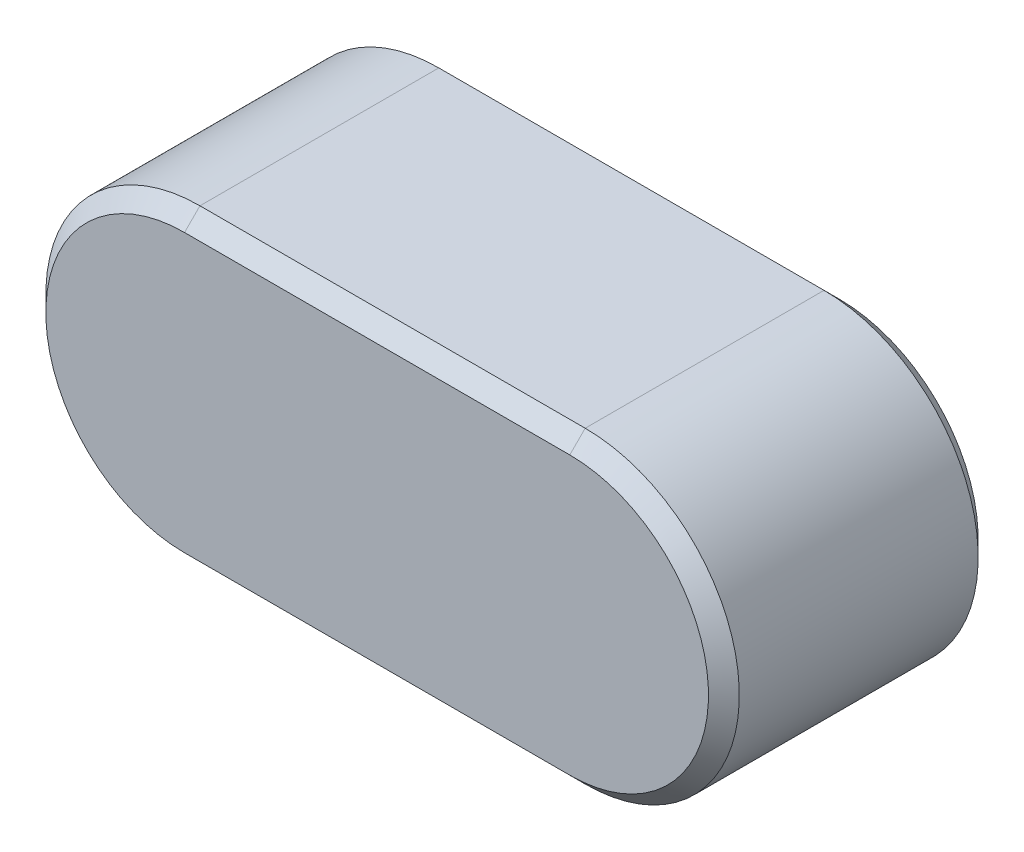
SolidWorks part; units mm, degrees
ref_plane "Front" through (0, 0, 0) normal (0, 0, 1) x (1, 0, 0)
ref_plane "Top" through (0, 0, 0) normal (0, 1, 0) x (1, 0, 0)
ref_plane "Right" through (0, 0, 0) normal (1, 0, 0) x (0, 0, -1)
other "Configuration Table"
sketch "Sketch1" plane through (0, 0, 0) normal (0, 0, 1) x (1, 0, 0)
  line L0 (-10, 4) -> (0, 4)
  line L1 (0, -4) -> (-10, -4)
  arc A0 (0, 4) -> (0, -4) centre (0, 0) cw
  arc A1 (-10, -4) -> (-10, 4) centre (-10, 0) cw
  dimension "L" = 18
  dimension "b" = 8
extrude "BaseKey" add sketch "Sketch1" along normal mid plane 7
sketch "Sketch2" plane through (0, 0, 0) normal (0, 0, 1) x (1, 0, 0)
  line L1 (-14, 4) -> (4, 4)
  line L2 (-14, 4) -> (-14, -4)
  line L3 (-14, -4) -> (4, -4)
  line L4 (4, 4) -> (4, -4)
  line L6 (0, -4) -> (-10, -4) construction
  line L7 (-10, 4) -> (0, 4) construction
  arc A2 (0, -4) -> (0, 4) centre (0, 0) ccw construction
  arc A3 (-10, 4) -> (-10, -4) centre (-10, 0) ccw construction
extrude "Extrude1" [suppressed] add sketch "Sketch2" along normal mid plane 7
sketch "Sketch3" plane through (0, 0, 0) normal (0, 0, 1) x (1, 0, 0)
  line L0 (4, 4) -> (-10, 4)
  line L1 (-10, -4) -> (4, -4)
  line L2 (4, -4) -> (4, 4)
  line L5 (-10, 4) -> (0, 4) construction
  arc A0 (-10, 4) -> (-10, -4) centre (-10, 0) ccw
  arc A1 (0, -4) -> (0, 4) centre (0, 0) ccw construction
  arc A4 (-10, 4) -> (-10, -4) centre (-10, 0) ccw construction
extrude "Extrude2" [suppressed] add sketch "Sketch3" along normal mid plane 7
chamfer "Chamfer1" distance 0.4 angle 45 8 edges at (4, 0, -3.5) (-5, -4, -3.5) (-14, 0, -3.5) (-5, 4, -3.5) (-14, 0, 3.5) (-5, -4, 3.5) (4, 0, 3.5) (-5, 4, 3.5)
equation "\"D1@Extrude1\"=\"h@BaseKey\""
equation "\"D1@Extrude2\"=\"h@BaseKey\""
